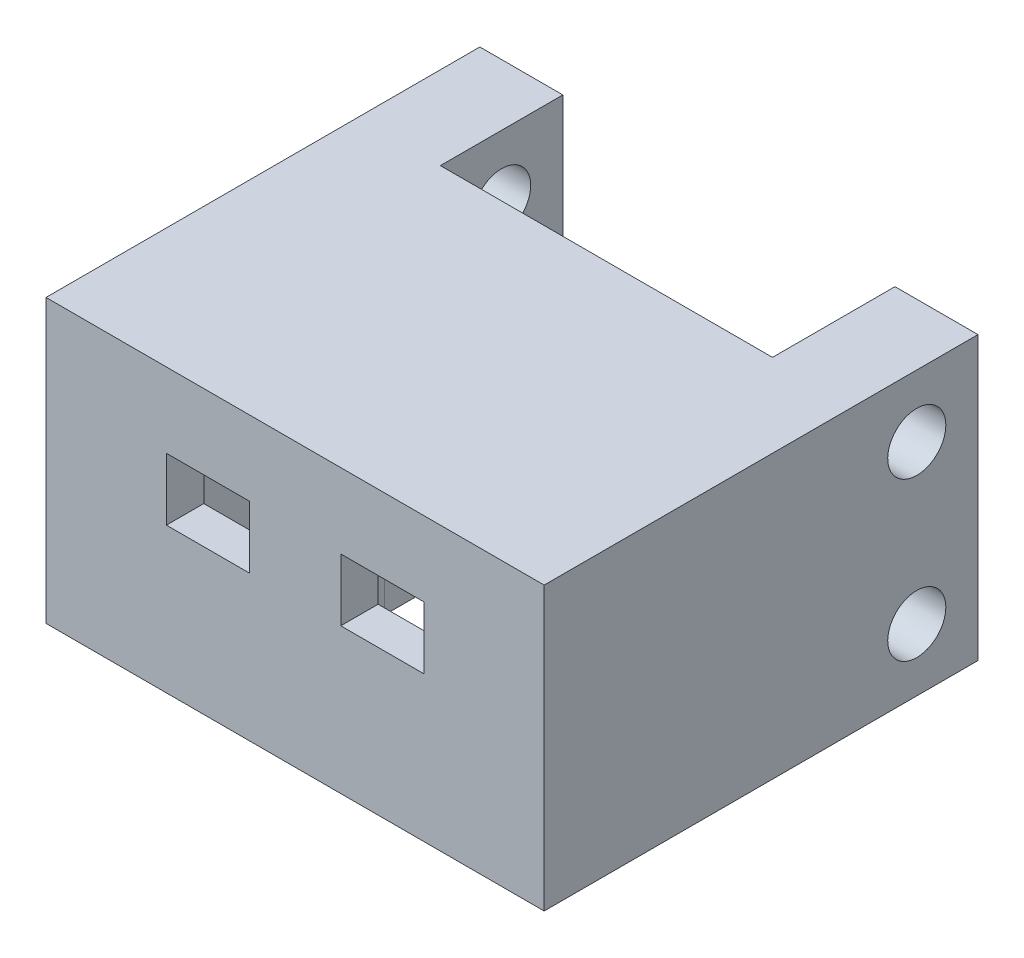
SolidWorks part; units mm, degrees
ref_plane "前视基准面" through (0, 0, 0) normal (0, 0, 1) x (1, 0, 0)
ref_plane "上视基准面" through (0, 0, 0) normal (0, 1, 0) x (1, 0, 0)
ref_plane "右视基准面" through (0, 0, 0) normal (1, 0, 0) x (0, 0, -1)
other "Configuration Table"
sketch "草图1" plane through (0, 0, 0) normal (0, 1, 0) x (1, 0, 0)
  line L0 (-4, 0) -> (4, 0) construction
  line L1 (-4, -4.25) -> (4, -4.25)
  line L2 (-4, -4.25) -> (-4, 3.25)
  line L3 (-4, 3.25) -> (4, 3.25)
  line L4 (4, -4.25) -> (4, 3.25)
  line L6 (-2.1, 0) -> (2.1, 0)
  line L7 (-2.1, 0) -> (-2.1, 3.25)
  line L8 (-2.1, 3.25) -> (2.1, 3.25)
  line L9 (2.1, 0) -> (2.1, 3.25)
  circle A0 centre (0, 0) radius 2.1
  dimension "D3" = 4.2
  dimension "D1" = 7.5
  dimension "D2" = 3.25
  dimension "D4" = 8
extrude "凸台-拉伸1" add sketch "草图1" along normal blind 1 contours L2 L3 L4 L1 | A0 | L9 L8 L7 L6
sketch "草图3" plane through (0, 1, 0) normal (0, 1, 0) x (1, 0, 0)
  line L0 (-4, -4.25) -> (4, -4.25) construction
  line L1 (-4, 3.25) -> (-3.3, 3.25)
  line L2 (-4, 3.25) -> (-4, -4.25)
  line L3 (-4, -4.25) -> (-3.3, -4.25)
  line L4 (-3.3, 3.25) -> (-3.3, -4.25)
  line L5 (-4, 3.25) -> (-2.1, 3.25) construction
  line L6 (4, -4.25) -> (3.3, -4.25)
  line L7 (4, -4.25) -> (4, 3.25)
  line L8 (4, 3.25) -> (3.3, 3.25)
  line L9 (3.3, -4.25) -> (3.3, 3.25)
  line L11 (-4, -4.25) -> (4, -4.25)
  line L12 (-4, -4.25) -> (-4, -3.35)
  line L13 (-4, -3.35) -> (4, -3.35)
  line L14 (4, -4.25) -> (4, -3.35)
  line M11 (-4, -4.25) -> (4, -4.25)
  dimension "D1" = 0.7
  dimension "D2" = 0.9
extrude "凸台-拉伸2" add sketch "草图3" along normal blind 4.8 contours L13 L4 L9 M11
sketch "草图4" plane through (0, 0, 4.25) normal (0, 0, 1) x (1, 0, 0)
  line L0 (-4, 0) -> (4, 0) construction
  line L1 (4, 5.8) -> (6, 5.8)
  line L2 (4, 5.8) -> (4, 0)
  line L3 (4, 0) -> (6, 0)
  line L4 (6, 5.8) -> (6, 0)
  line L5 (-4, 5.8) -> (-6, 5.8)
  line L6 (-4, 5.8) -> (-4, 0)
  line L7 (-4, 0) -> (-6, 0)
  line L8 (-6, 5.8) -> (-6, 0)
  dimension "D1" = 2
extrude "凸台-拉伸3" add sketch "草图4" against normal blind 10.45
sketch "草图5" plane through (0, 5.8, 0) normal (0, 1, 0) x (1, 0, 0)
  line L0 (6, 6.2) -> (6, -4.25) construction
  line L1 (-6, -4.25) -> (6, -4.25)
  line L2 (-6, -4.25) -> (-6, 3.25)
  line L3 (-6, 3.25) -> (6, 3.25)
  line L4 (6, -4.25) -> (6, 3.25)
  line L5 (-4, 6.2) -> (-4, 3.25) construction
  line L6 (-6, 6.2) -> (-4, 6.2)
  line L7 (-6, 6.2) -> (-6, 3.25)
  line L8 (-6, 3.25) -> (-4, 3.25)
  line L9 (-4, 6.2) -> (-4, 3.25)
  line L10 (4, 6.2) -> (6, 6.2)
  line L11 (4, 6.2) -> (4, 3.25)
  line L12 (4, 3.25) -> (6, 3.25)
  line L13 (6, 6.2) -> (6, 3.25)
  line M5 (3.3, -3.35) -> (-3.3, -3.35)
  line M6 (-3.3, -3.35) -> (-3.3, 3.25)
  line M7 (-3.3, 3.25) -> (-4, 3.25)
  line M8 (-4, 3.25) -> (-4, 6.2)
  line M9 (-4, 6.2) -> (-6, 6.2)
  line M10 (-6, 6.2) -> (-6, -4.25)
  line M11 (-6, -4.25) -> (6, -4.25)
  line M12 (6, -4.25) -> (6, 6.2)
  line M13 (6, 6.2) -> (4, 6.2)
  line M14 (4, 6.2) -> (4, 3.25)
  line M15 (4, 3.25) -> (3.3, 3.25)
  line M16 (3.3, 3.25) -> (3.3, -3.35)
  dimension "D1" = 7.5
extrude "凸台-拉伸4" add sketch "草图5" along normal blind 1 contours L3 M10 M11 M12 M15 M16 M5 M6 M7 | L3 M6 M5 M16 | L3 M10 M8 M9 | L3 M14 M12 M13 | L13 L10 L11 L12 | L8 L9 L6 L7 | L2 L1 L4
sketch "草图6" plane through (0, 0, 4.25) normal (0, 0, 1) x (1, 0, 0)
  line L0 (-6, 6.8) -> (-6, 0) construction
  line L1 (-3.1, 5) -> (-1.1, 5)
  line L2 (-3.1, 5) -> (-3.1, 3.5)
  line L3 (-3.1, 3.5) -> (-1.1, 3.5)
  line L4 (-1.1, 5) -> (-1.1, 3.5)
  line L5 (1.1, 5) -> (3.1, 5)
  line L6 (1.1, 5) -> (1.1, 3.5)
  line L7 (1.1, 3.5) -> (3.1, 3.5)
  line L8 (3.1, 5) -> (3.1, 3.5)
  line L9 (6, 0) -> (6, 6.8) construction
  line L10 (-6, 6.8) -> (6, 6.8) construction
  point P10 (-3.1, 4.25)
  dimension "D1" = 2.9
  dimension "D2" = 2.9
  dimension "D3" = 2
  dimension "D4" = 1.8
  dimension "D5" = 1.5
extrude "切除-拉伸1" cut sketch "草图6" against normal through all
sketch "草图7" plane through (-6, 0, 0) normal (-1, 0, 0) x (0, 0, 1)
  line L0 (-6.2, 6.8) -> (-6.2, 0) construction
  line L1 (-6.2, 0) -> (4.25, 0) construction
  line L2 (-6.2, 6.8) -> (4.25, 6.8) construction
  circle A0 centre (-4.725, 5.3) radius 0.7
  circle A1 centre (-4.725, 1.5) radius 0.7
  dimension "D1" = 1.4
  dimension "D2" = 1.475
  dimension "D3" = 1.5
  dimension "D4" = 1.5
extrude "切除-拉伸2" cut sketch "草图7" against normal through all contours A0 | A1
